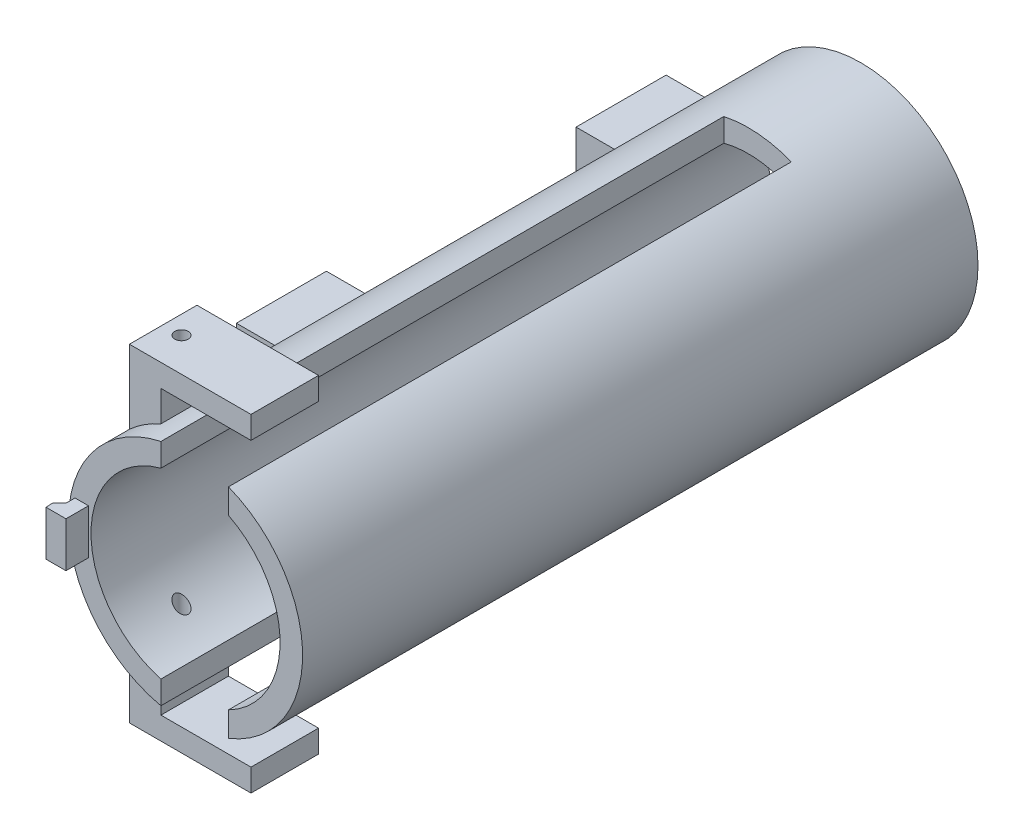
SolidWorks part; units mm, degrees
ref_plane "Plano frontal" through (0, 0, 0) normal (0, 0, 1) x (1, 0, 0)
ref_plane "Plano superior" through (0, 0, 0) normal (0, 1, 0) x (1, 0, 0)
ref_plane "Plano direito" through (0, 0, 0) normal (1, 0, 0) x (0, 0, -1)
sketch "Esboço1" plane through (0, 0, 0) normal (0, 0, 1) x (1, 0, 0)
  circle A0 centre (0, 0) radius 21
  circle A1 centre (0, 0) radius 26
  dimension "D1" = 5
  dimension "D2" = 42
extrude "Ressalto-extrusão1" add sketch "Esboço1" along normal blind 150
sketch3d "3DSketch1"
  point P0 (3.6336, -25.7448, 55.7114)
ref_plane "Plano1" through (0, -27.2211, 0) normal (0, -1, 0) x (0, 0, -1)
sketch "Esboço3" plane through (0, -27.2211, 0) normal (0, -1, 0) x (0, 0, -1)
  line L0 (-150, -5.4656) -> (-150, 9.5344)
  line L1 (-150, 26) -> (-150, -26) construction
  line L2 (-150, 9.5344) -> (-25, 9.5344)
  line L3 (-25, 9.5344) -> (-25, -5.4656)
  line L4 (-25, -5.4656) -> (-150, -5.4656)
  line L5 (0, -26) -> (0, 26) construction
  point P5 (-150, 2.0344)
  dimension "D1" = 15
  dimension "D2" = 25
extrude "Corte-extrusão1" cut sketch "Esboço3" against normal through all both and the other way through all
sketch "Esboço4" plane through (0, -27.2211, 0) normal (0, -1, 0) x (0, 0, -1)
  line L0 (-25, -5.4656) -> (-150, -5.4656) construction
  line L1 (-145, -10.4656) -> (-130, -10.4656)
  line L2 (-145, -10.4656) -> (-145, -17.4656)
  line L3 (-145, -17.4656) -> (-130, -17.4656)
  line L4 (-130, -10.4656) -> (-130, -17.4656)
  line L5 (-150, -5.4656) -> (-150, -26) construction
  dimension "D1" = 5
  dimension "D2" = 5
  dimension "D3" = 15
  dimension "D4" = 7
extrude "Ressalto-extrusão2" add sketch "Esboço4" against normal up to next
sketch "Esboço5" plane through (0, -27.2211, 0) normal (0, -1, 0) x (1, 0, 0)
  line L1 (-10.4656, 145) -> (-17.4656, 145)
  line L2 (-10.4656, 145) -> (-10.4656, 130)
  line L3 (-10.4656, 130) -> (-17.4656, 130)
  line L4 (-17.4656, 145) -> (-17.4656, 130)
extrude "Ressalto-extrusão3" add sketch "Esboço5" along normal blind 10
sketch "Esboço6" plane through (-10.4656, 0, 0) normal (1, 0, 0) x (0, 0, -1)
  line L0 (-130, -23.8007) -> (-130, -37.2211) construction
  line L1 (-145, -37.2211) -> (-130, -37.2211)
  line L2 (-145, -37.2211) -> (-145, -32.2211)
  line L3 (-145, -32.2211) -> (-130, -32.2211)
  line L4 (-130, -37.2211) -> (-130, -32.2211)
  dimension "D1" = 5
extrude "Ressalto-extrusão4" add sketch "Esboço6" along normal blind 20
sketch3d "3DSketch2"
  point P0 (4.427, 25.6203, 12.7577)
ref_plane "Plano3" through (0, 25.6203, 0) normal (0, 1, 0) x (0, 0, 1)
sketch "Esboço7" plane through (0, 25.6203, 0) normal (0, 1, 0) x (0, 0, 1)
  line L0 (150, -26) -> (150, -5.4656) construction
  line L1 (130, -10.4656) -> (145, -10.4656)
  line L2 (130, -10.4656) -> (130, -17.4656)
  line L3 (130, -17.4656) -> (145, -17.4656)
  line L4 (145, -10.4656) -> (145, -17.4656)
  line L5 (150, -5.4656) -> (25, -5.4656) construction
  dimension "D1" = 15
  dimension "D2" = 5
  dimension "D3" = 5
  dimension "D4" = 7
extrude "Ressalto-extrusão5" add sketch "Esboço7" against normal up to next
sketch "Esboço8" plane through (0, 25.6203, 0) normal (0, 1, 0) x (1, 0, 0)
  line L1 (-17.4656, -130) -> (-10.4656, -130)
  line L2 (-17.4656, -130) -> (-17.4656, -145)
  line L3 (-17.4656, -145) -> (-10.4656, -145)
  line L4 (-10.4656, -130) -> (-10.4656, -145)
extrude "Ressalto-extrusão6" add sketch "Esboço8" along normal blind 10
sketch "Esboço9" plane through (-10.4656, 0, 0) normal (1, 0, 0) x (0, 0, -1)
  line L5 (-130, 23.8007) -> (-130, 35.6203) construction
  line L6 (-145, 35.6203) -> (-130, 35.6203)
  line L7 (-145, 35.6203) -> (-145, 30.6203)
  line L8 (-145, 30.6203) -> (-130, 30.6203)
  line L9 (-130, 35.6203) -> (-130, 30.6203)
  dimension "D1" = 5
extrude "Ressalto-extrusão7" add sketch "Esboço9" along normal blind 20
sketch "Esboço10" plane through (0, -37.2211, 0) normal (0, -1, 0) x (1, 0, 0)
  line L0 (-17.4656, 137.5) -> (9.5344, 137.5) construction
  line L1 (-17.4656, 145) -> (-17.4656, 130) construction
  line L2 (9.5344, 145) -> (9.5344, 130) construction
  circle A0 centre (-13.4052, 137.5) radius 1.5
extrude "Corte-extrusão2" cut sketch "Esboço10" against normal through all both and the other way through all
sketch3d "3DSketch3"
  point P0 (-25.9916, -0.662, 86.0184)
ref_plane "Plano4" through (-25.9916, 0, 0) normal (-1, 0, 0) x (0, -1, 0)
sketch "Esboço14" plane through (-25.9916, 0, 0) normal (-1, 0, 0) x (0, -1, 0)
  line L0 (-19.2601, 130) -> (-19.2601, 0) construction
  line L1 (-26, 0) -> (26, 0) construction
  line L2 (-19.2601, 130) -> (19.2601, 130) construction
  line L3 (19.2601, 130) -> (19.2601, 0) construction
  line L4 (19.2601, 0) -> (-19.2601, 0) construction
  line L5 (0, 130) -> (0, 0) construction
  line L6 (-19.2601, 112.7211) -> (-4.2601, 112.7211)
  line L7 (-19.2601, 112.7211) -> (-19.2601, 92.7211)
  line L8 (-19.2601, 92.7211) -> (-4.2601, 92.7211)
  line L9 (-4.2601, 112.7211) -> (-4.2601, 92.7211)
  line L10 (-19.2601, 65) -> (19.2601, 65) construction
  line L11 (19.2601, 92.7211) -> (4.2601, 92.7211)
  line L12 (4.2601, 112.7211) -> (4.2601, 92.7211)
  line L13 (19.2601, 112.7211) -> (4.2601, 112.7211)
  line L14 (19.2601, 112.7211) -> (19.2601, 92.7211)
  line L15 (19.2601, 17.2789) -> (19.2601, 37.2789)
  line L16 (19.2601, 17.2789) -> (4.2601, 17.2789)
  line L17 (4.2601, 17.2789) -> (4.2601, 37.2789)
  line L18 (19.2601, 37.2789) -> (4.2601, 37.2789)
  line L19 (-19.2601, 37.2789) -> (-4.2601, 37.2789)
  line L20 (-4.2601, 17.2789) -> (-4.2601, 37.2789)
  line L21 (-19.2601, 17.2789) -> (-4.2601, 17.2789)
  line L22 (-19.2601, 17.2789) -> (-19.2601, 37.2789)
  dimension "D1" = 15
  dimension "D2" = 20
extrude "Ressalto-extrusão8" add sketch "Esboço14" against normal up to next
sketch "Esboço15" plane through (-25.9916, 0, 0) normal (-1, 0, 0) x (0, 0, 1)
  line L0 (17.2789, 11.7601) -> (112.7211, 11.7601) construction
  line L1 (17.2789, 19.2601) -> (17.2789, 4.2601) construction
  line L2 (112.7211, 4.2601) -> (112.7211, 19.2601) construction
  line L3 (102.7211, 19.2601) -> (102.7211, -19.2601) construction
  line L4 (112.7211, 19.2601) -> (92.7211, 19.2601) construction
  line L5 (92.7211, -19.2601) -> (112.7211, -19.2601) construction
  line L6 (112.7211, -11.7601) -> (17.2789, -11.7601) construction
  line L7 (112.7211, -19.2601) -> (112.7211, -4.2601) construction
  line L8 (17.2789, -4.2601) -> (17.2789, -19.2601) construction
  line L9 (27.2789, 19.2601) -> (27.2789, -19.2601) construction
  line L10 (37.2789, 19.2601) -> (17.2789, 19.2601) construction
  line L11 (17.2789, -19.2601) -> (37.2789, -19.2601) construction
  line L12 (65, 41.4744) -> (65, -47.7689) construction
  line L13 (-11.4678, 0) -> (157.6888, 0) construction
  line L14 (150, -25.419) -> (150, 25.419) construction
  line L15 (0, 26) -> (0, -26) construction
  circle A0 centre (27.2789, 11.7601) radius 1.75
  circle A1 centre (102.7211, 11.7601) radius 1.75
  circle A2 centre (102.7211, -11.7601) radius 1.75
  circle A3 centre (27.2789, -11.7601) radius 1.75
  dimension "D1" = 47.2789
  dimension "D2" = 23.5203
  dimension "D3" = 75.4423
  dimension "D4" = 27.2789
  dimension "D5" = 38.5203
extrude "Corte-extrusão3" cut sketch "Esboço15" against normal blind 15
sketch "Esboço17" plane through (0, -27.2211, 0) normal (0, -1, 0) x (0, 0, -1)
  line L0 (-25, 2.0344) -> (0, 2.0344) construction
  line L1 (-25, 9.5344) -> (-25, -5.4656) construction
  line L2 (0, -26) -> (0, 26) construction
  circle A0 centre (-19, 2.0344) radius 1.75
  circle A1 centre (-6, 2.0344) radius 1.75
  dimension "D1" = 6
  dimension "D2" = 13
extrude "Corte-extrusão4" cut sketch "Esboço17" along normal blind 3 and the other way blind 18
sketch3d "3DSketch4"
  point P0 (2.6209, 20.8358, 10.7292)
ref_plane "Plano5" through (0, 20.8358, 0) normal (0, 1, 0) x (0, 0, 1)
sketch "Esboço18" plane through (0, 20.8358, 0) normal (0, 1, 0) x (0, 0, 1)
  line L1 (9, 0.3024) -> (9, 3.7665)
  line L2 (9, 3.7665) -> (6, 5.4985)
  line L3 (6, 5.4985) -> (3, 3.7665)
  line L4 (3, 3.7665) -> (3, 0.3024)
  line L5 (3, 0.3024) -> (6, -1.4297)
  line L6 (6, -1.4297) -> (9, 0.3024)
  line L7 (21.989, 3.7853) -> (18.9782, 5.4984)
  line L8 (18.9782, 5.4984) -> (15.9891, 3.7475)
  line L9 (15.9891, 3.7475) -> (16.011, 0.2835)
  line L10 (16.011, 0.2835) -> (19.0218, -1.4296)
  line L11 (19.0218, -1.4296) -> (22.0109, 0.3213)
  line L12 (22.0109, 0.3213) -> (21.989, 3.7853)
  circle A0 centre (6, 2.0344) radius 3 construction
  circle A1 centre (19, 2.0344) radius 3 construction
  dimension "D1" = 6
  dimension "D2" = 6
extrude "Corte-extrusão5" cut sketch "Esboço18" against normal blind 3.5 from offset 41.1 offset against normal yes
sketch "Esboço19" plane through (0, 0, 150) normal (0, 0, 1) x (1, 0, 0)
  line L0 (-25.9916, 0) -> (26, 0) construction
  line L1 (-25.9916, 53.8209) -> (-25.9916, -53.8209) construction
  line L2 (-24.5572, 5) -> (-21.5572, 5)
  line L3 (-25.5572, 5) -> (-21.5572, 5)
  line L4 (-25.5572, 5) -> (-25.5572, -5)
  line L5 (-25.5572, -5) -> (-21.5572, -5)
  line L6 (-21.5572, 5) -> (-21.5572, -5)
  line L7 (-21.5572, 5) -> (-24.5572, 5)
  line L8 (-21.5572, 5) -> (-21.5572, -5)
  line L9 (-21.5572, -5) -> (-24.5572, -5)
  line L10 (-24.5572, 5) -> (-24.5572, -5)
  circle A0 centre (0, 0) radius 26 construction
  dimension "D1" = 10
  dimension "D2" = 5
  dimension "D3" = 4
  dimension "D4" = 3
extrude "Ressalto-extrusão9" add sketch "Esboço19" along normal blind 5 contours L10 L0 L6 L2 | L0 L10 L5 L8
sketch "Esboço20" plane through (0, 5, 0) normal (0, 1, 0) x (1, 0, 0)
  line L0 (-24.5572, -155) -> (-24.5572, -152)
  line L1 (-24.5572, -155) -> (-24.5572, -150) construction
  line L2 (-24.5572, -152) -> (-27.5572, -155)
  line L3 (-27.5572, -155) -> (-24.5572, -155)
  dimension "D1" = 3
  dimension "D2" = 3
extrude "Ressalto-extrusão10" add sketch "Esboço20" against normal blind 10 contours L3 L0 L2
sketch "Esboço23" plane through (0, -5, 0) normal (0, -1, 0) x (1, 0, 0)
  line L0 (-27.5572, 155) -> (-25.9916, 155)
  line L1 (-25.9916, 53.8209) -> (-25.9916, -53.8209) construction
  line L2 (-27.5572, 155) -> (-21.5572, 155) construction
  line L3 (-25.9916, 155) -> (-26.0572, 153.5)
  line L4 (-24.5572, 152) -> (-27.5572, 155) construction
  line L5 (-26.0572, 153.5) -> (-27.5572, 155)
extrude "Corte-extrusão6" cut sketch "Esboço23" against normal through all contours L5 L0 L3
